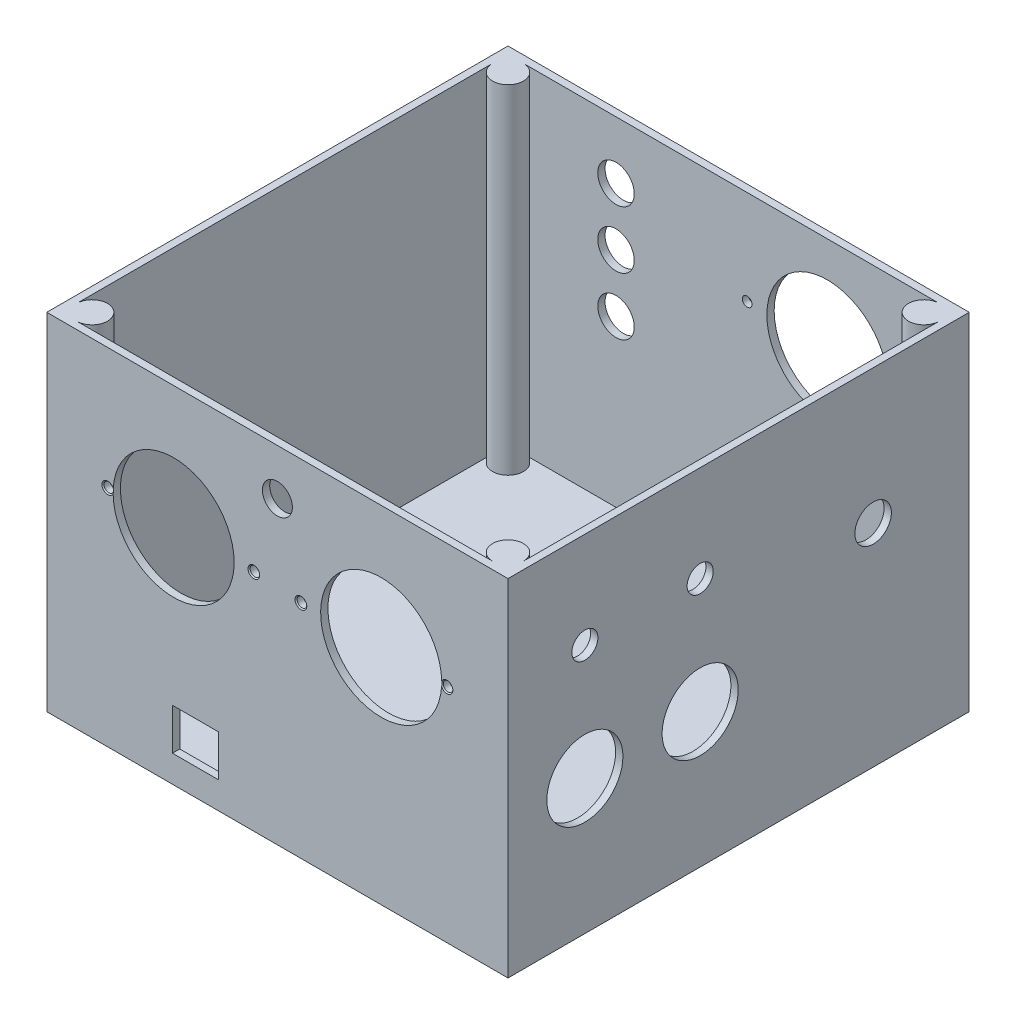
SolidWorks part; units mm, degrees
ref_plane "Front Plane" through (0, 0, 0) normal (0, 0, 1) x (1, 0, 0)
ref_plane "Top Plane" through (0, 0, 0) normal (0, 1, 0) x (1, 0, 0)
ref_plane "Right Plane" through (0, 0, 0) normal (1, 0, 0) x (0, 0, -1)
sketch "Sketch1" plane through (0, 0, 0) normal (0, 1, 0) x (1, 0, 0)
  line L1 (0, 0) -> (120, 0)
  line L2 (0, 0) -> (0, 120)
  line L3 (0, 120) -> (120, 120)
  line L4 (120, 0) -> (120, 120)
  dimension "D1" = 120
  dimension "D2" = 120
extrude "Boss-Extrude1" add sketch "Sketch1" along normal blind 90
sketch "Sketch2" plane through (0, 90, 0) normal (0, 1, 0) x (1, 0, 0)
  line L0 (120, 120) -> (0, 120) construction
  line L1 (1.9, 118.1) -> (118.1, 118.1)
  line L2 (1.9, 118.1) -> (1.9, 1.9)
  line L3 (1.9, 1.9) -> (118.1, 1.9)
  line L4 (118.1, 118.1) -> (118.1, 1.9)
  line L5 (120, 0) -> (120, 120) construction
  dimension "D1" = 116.2
  dimension "D2" = 116.2
  dimension "D3" = 1.9
  dimension "D4" = 1.9
extrude "Cut-Extrude1" cut sketch "Sketch2" against normal blind 88
sketch "Sketch3" plane through (0, 2, 0) normal (0, 1, 0) x (1, 0, 0)
  line L0 (118.1, 118.1) -> (1.9, 118.1) construction
  line L1 (1.9, 118.1) -> (1.9, 1.9) construction
  line L2 (5.9, 118.1) -> (1.9, 118.1)
  line L3 (1.9, 118.1) -> (1.9, 114.1)
  line L4 (60, 234.3) -> (60, 1.9)
  line L5 (1.9, 1.9) -> (118.1, 1.9) construction
  line L6 (114.1, 118.1) -> (118.1, 118.1)
  line L7 (118.1, 118.1) -> (118.1, 114.1)
  line L8 (-114.3, 60) -> (118.1, 60)
  line L10 (118.1, 1.9) -> (118.1, 118.1) construction
  line L11 (118.1, 1.9) -> (118.1, 5.9)
  line L12 (114.1, 1.9) -> (118.1, 1.9)
  line L13 (1.9, 1.9) -> (1.9, 5.9)
  line L14 (5.9, 1.9) -> (1.9, 1.9)
  arc A0 (1.9, 114.1) -> (5.9, 118.1) centre (5.9, 114.1) ccw
  arc A1 (118.1, 114.1) -> (114.1, 118.1) centre (114.1, 114.1) cw
  arc A2 (118.1, 5.9) -> (114.1, 1.9) centre (114.1, 5.9) ccw
  arc A3 (1.9, 5.9) -> (5.9, 1.9) centre (5.9, 5.9) cw
  point P14 (60, 118.1)
  point P21 (1.9, 60)
  dimension "D1" = 8
extrude "Boss-Extrude2" add sketch "Sketch3" along normal blind 88 contours A0 L2 L3 | A1 L6 L7 | L12 L11 A2 | A3 L14 L13
sketch "Sketch4" plane through (0, 0, 0) normal (0, 0, 1) x (1, 0, 0)
  line L0 (0, 90) -> (0, 0) construction
  line L1 (32.7, 17.8) -> (44.7, 17.8)
  line L2 (32.7, 17.8) -> (32.7, 7)
  line L3 (32.7, 7) -> (44.7, 7)
  line L4 (44.7, 17.8) -> (44.7, 7)
  line L5 (0, 0) -> (120, 0) construction
  line L6 (120, 90) -> (120, 0) construction
  line L7 (0, 90) -> (120, 90) construction
  line L8 (60, 90) -> (60, 0) construction
  circle A0 centre (60, 78) radius 3.9
  circle A8 centre (33, 58) radius 15.75
  circle A9 centre (87, 58) radius 15.75
  dimension "D5" = 12
  dimension "D8" = 31.5
  dimension "D12" = 31.5
  dimension "D7" = 7.8
  dimension "D1" = 12
  dimension "D2" = 10.8
  dimension "D3" = 44.7
  dimension "D4" = 7
  dimension "D6" = 60
  dimension "D9" = 33
  dimension "D10" = 33
  dimension "D11" = 32
sketch "Sketch5" plane through (0, 0, -120) normal (0, 0, 1) x (1, 0, 0)
  line L1 (120, 90) -> (120, 0) construction
  line L3 (0, 90) -> (120, 90) construction
  line L4 (0, 90) -> (0, 0) construction
  circle A2 centre (30, 75) radius 4.75
  circle A3 centre (85, 65) radius 15.75
  circle A6 centre (30, 60) radius 4.75
  circle A7 centre (30, 45) radius 4.75
  dimension "D1" = 30
  dimension "D2" = 9.5
  dimension "D4" = 31.5
  dimension "D3" = 15
  dimension "D5" = 3
  dimension "D7" = 35
  dimension "D8" = 25
extrude "Cut-Extrude2" cut sketch "Sketch5" along normal up to next
extrude "Cut-Extrude3" cut sketch "Sketch4" against normal up to next
sketch "Sketch6" plane through (120, 0, 0) normal (1, 0, 0) x (0, 0, -1)
  line L0 (0, 90) -> (0, 0) construction
  line L1 (0, 90) -> (120, 90) construction
  line L2 (120, 90) -> (120, 0) construction
  circle A0 centre (95, 55) radius 4.75
  circle A1 centre (20, 65) radius 3.4
  circle A2 centre (50, 65) radius 3.4
  circle A3 centre (20, 35) radius 9.9
  circle A4 centre (50, 35) radius 9.9
  dimension "D1" = 9.5
  dimension "D2" = 6.8
  dimension "D3" = 6.8
  dimension "D4" = 19.8
  dimension "D5" = 19.8
  dimension "D6" = 20
  dimension "D7" = 30
  dimension "D8" = 30
  dimension "D9" = 25
  dimension "D10" = 35
  dimension "D11" = 25
extrude "Cut-Extrude4" cut sketch "Sketch6" against normal up to next
hole_wizard "M3 Tapped Hole1" positions "Sketch7" profile "Sketch8" tap size "M3" standard "ISO" end condition through all
sketch "Sketch7" plane through (44.5177, 2, -162.2468) normal (0, 1, 0) x (1, 0, 0)
  point P0 (-18.4177, -139.4468)
  point P3 (-3.2177, -88.6468)
  point P6 (24.6823, -88.6468)
  point P9 (29.3823, -140.5468)
sketch "Sketch8" plane through (26.1, 2, -22.8) normal (1, 0, 0) x (0, 0, 1)
  line L0 (0, 0) -> (0, 2)
  line L1 (0, 2) -> (1.25, 2)
  line L2 (1.25, 2) -> (1.25, 0.275)
  line L3 (1.25, 0.275) -> (1.525, 0)
  line L4 (1.525, 0) -> (0, 0)
  line L5 (-1.25, 0.275) -> (-1.525, 0) construction
  line L6 (0, -6.35) -> (0, 107.95) construction
  dimension "Thru Tap Drill Dia." = 2.5
  dimension "Thru Tap Drill Depth" = 2
  dimension "Near C'Sink Dia." = 3.05
  dimension "Near C'Sink Angle" = 90
cosmetic thread "Hole Thread1" parameters "D2"=3
cosmetic thread "Hole Thread2" parameters "D2"=3
cosmetic thread "Hole Thread3" parameters "D2"=3
cosmetic thread "Hole Thread4" parameters "D2"=3
hole_wizard "M3 Tapped Hole3" positions "Sketch11" profile "Sketch12" tap size "M3" standard "ISO"
sketch "Sketch11" plane through (44.5177, -28.7557, 0) normal (0, 0, 1) x (1, 0, 0)
  point P0 (-28.6467, 87.1249)
  point P3 (9.3596, 87.1742)
  point P34 (21.605, 86.3372)
  point P37 (59.6113, 86.3865)
sketch "Sketch12" plane through (15.871, 58.3692, 0) normal (1, 0, 0) x (0, -1, 0)
  line L0 (0, 0) -> (0, 8.2511)
  line L1 (0, 8.2511) -> (1.25, 7.5)
  line L2 (1.25, 7.5) -> (1.25, 0.275)
  line L3 (1.25, 0.275) -> (1.525, 0)
  line L4 (1.525, 0) -> (0, 0)
  line L5 (-1.25, 0.275) -> (-1.525, 0) construction
  line L6 (0, 8.2511) -> (-1.25, 7.5) construction
  line L7 (0, -6.35) -> (0, 107.95) construction
  dimension "Tap Drill Dia." = 2.5
  dimension "Tap Drill Depth" = 7.5
  dimension "Near C'Sink Dia." = 3.05
  dimension "Near C'Sink Angle" = 90
  dimension "Drill Angle" = 118
cosmetic thread "Hole Thread9" parameters "D1"=1.9, "D2"=3
cosmetic thread "Hole Thread10" parameters "D1"=1.9, "D2"=3
cosmetic thread "Hole Thread11" parameters "D1"=1.9, "D2"=3
cosmetic thread "Hole Thread12" parameters "D1"=1.9, "D2"=3
hole_wizard "M3 Tapped Hole4" positions "Sketch13" profile "Sketch14" tap size "M3" standard "ISO"
sketch "Sketch13" plane through (44.5177, -28.7557, -120) normal (0, 0, -1) x (-1, 0, 0)
  point P0 (-57.6113, 94.1249)
  point P3 (-19.605, 94.1742)
sketch "Sketch14" plane through (102.129, 65.3692, -120) normal (1, 0, 0) x (0, 1, 0)
  line L0 (0, 0) -> (0, 8.2511)
  line L1 (0, 8.2511) -> (1.25, 7.5)
  line L2 (1.25, 7.5) -> (1.25, 0.275)
  line L3 (1.25, 0.275) -> (1.525, 0)
  line L4 (1.525, 0) -> (0, 0)
  line L5 (-1.25, 0.275) -> (-1.525, 0) construction
  line L6 (0, 8.2511) -> (-1.25, 7.5) construction
  line L7 (0, -6.35) -> (0, 107.95) construction
  dimension "Tap Drill Dia." = 2.5
  dimension "Tap Drill Depth" = 7.5
  dimension "Near C'Sink Dia." = 3.05
  dimension "Near C'Sink Angle" = 90
  dimension "Drill Angle" = 118
cosmetic thread "Hole Thread13" parameters "D1"=1.9, "D2"=3
cosmetic thread "Hole Thread14" parameters "D1"=1.9, "D2"=3
